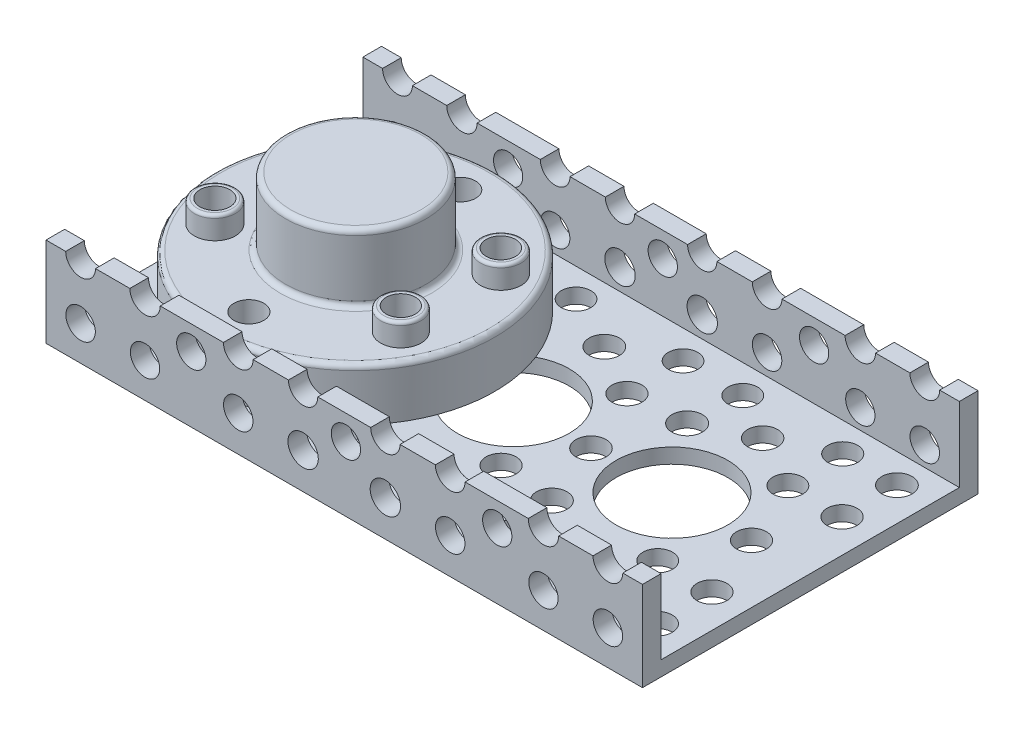
SolidWorks part; units mm, degrees
ref_plane "Front Plane" through (0, 0, 0) normal (0, 0, 1) x (1, 0, 0)
ref_plane "Top Plane" through (0, 0, 0) normal (0, 1, 0) x (1, 0, 0)
ref_plane "Right Plane" through (0, 0, 0) normal (1, 0, 0) x (0, 0, -1)
sketch "Sketch1" plane through (0, 0, 0) normal (0, 1, 0) x (1, 0, 0)
  line L1 (-56.0638, 18.2447) -> (23.9362, 18.2447)
  line L2 (-56.0638, 18.2447) -> (-56.0638, -26.7553)
  line L3 (-56.0638, -26.7553) -> (23.9362, -26.7553)
  line L4 (23.9362, 18.2447) -> (23.9362, -26.7553)
  dimension "D1" = 80
  dimension "D2" = 45
extrude "Boss-Extrude1" add sketch "Sketch1" along normal blind 2
sketch "Sketch2" plane through (0, 2, 0) normal (0, 1, 0) x (1, 0, 0)
  line L0 (-56.0638, 18.2447) -> (-56.0638, -26.7553) construction
  line L1 (-56.0638, -24.2553) -> (23.9362, -24.2553)
  line L2 (-56.0638, -24.2553) -> (-56.0638, -26.7553)
  line L3 (-56.0638, -26.7553) -> (23.9362, -26.7553)
  line L4 (23.9362, -24.2553) -> (23.9362, -26.7553)
  line L5 (-56.0638, -4.2553) -> (26.7837, -4.2553)
  line L6 (-56.0638, 18.2447) -> (23.9362, 18.2447)
  line L7 (23.9362, 15.7447) -> (23.9362, 18.2447)
  line L8 (-56.0638, 15.7447) -> (23.9362, 15.7447)
  line L9 (-56.0638, 15.7447) -> (-56.0638, 18.2447)
  line M6 (-56.0638, 18.2447) -> (-56.0638, -26.7553)
  line M7 (-56.0638, -26.7553) -> (23.9362, -26.7553)
  line M8 (23.9362, -26.7553) -> (23.9362, 18.2447)
  line M9 (23.9362, 18.2447) -> (-56.0638, 18.2447)
  dimension "D1" = 2.5
extrude "Boss-Extrude2" add sketch "Sketch2" along normal blind 10 contours L8 M6 M8 M9 | L1 M6 M7 M8
sketch "Sketch3" plane through (0, 2, 0) normal (0, 1, 0) x (1, 0, 0)
  line L0 (-56.0638, -4.2553) -> (26.7837, -4.2553) construction
  line L1 (-16.0638, 15.7447) -> (-16.0638, -15.7208)
  line L2 (-56.0638, 15.7447) -> (23.9362, 15.7447) construction
  circle A0 centre (-37.1174, -4.2553) radius 7.5
  circle A1 centre (-16.0191, -4.1212) radius 7.5
  circle A2 centre (5.258, -4.1212) radius 7.5
extrude "Cut-Extrude1" cut sketch "Sketch3" against normal blind 4 contours A0 | L1 A1 | L1 A1 | A2
sketch "Sketch4" plane through (0, 2, 0) normal (0, 1, 0) x (1, 0, 0)
  circle A0 centre (-48.1015, -4.382) radius 2
  circle A1 centre (-26.5885, -4.3897) radius 1.9841
  circle A2 centre (-5.3351, -4.3897) radius 2.0194
  circle A3 centre (16.1333, -4.3274) radius 2.0071
extrude "Cut-Extrude2" cut sketch "Sketch4" against normal blind 4 contours A0 | A1 | A2 | A3
sketch "Sketch5" plane through (0, 2, 0) normal (0, 1, 0) x (1, 0, 0)
  line L0 (-16.0638, 15.7447) -> (-16.0638, -15.8512)
  line L1 (-56.0638, 15.7447) -> (23.9362, 15.7447) construction
  line L2 (-56.0638, 15.7447) -> (23.9362, 15.7447)
  line L3 (23.9362, -4.2553) -> (1.0243, -4.2553)
  line L4 (-56.0638, -4.2553) -> (26.7837, -4.2553) construction
  circle A0 centre (12.2086, 4.4705) radius 1.9878
  circle A1 centre (19.4763, 4.4705) radius 2.0098
  circle A2 centre (12.2086, 11.8307) radius 1.9991
  circle A3 centre (19.4763, 11.8307) radius 2.0289
  circle A4 centre (-51.604, 4.4705) radius 2.0098
  circle A5 centre (-44.3363, 4.4705) radius 1.9878
  circle A6 centre (-51.604, 11.8307) radius 2.0289
  circle A7 centre (-44.3363, 11.8307) radius 1.9991
  circle A8 centre (-44.3363, -12.9811) radius 1.9878
  circle A9 centre (-51.604, -12.9811) radius 2.0098
  circle A10 centre (-51.604, -20.3414) radius 2.0289
  circle A11 centre (-44.3363, -20.3414) radius 1.9991
  circle A12 centre (12.2086, -12.9811) radius 1.9878
  circle A13 centre (19.4763, -12.9811) radius 2.0098
  circle A14 centre (19.4763, -20.3414) radius 2.0289
  circle A15 centre (12.2086, -20.3414) radius 1.9991
  point P15 (-16.0638, 15.7447)
extrude "Cut-Extrude3" cut sketch "Sketch5" against normal blind 4 contours A6 | A7 | A4 | A5 | A2 | A3 | A0 | A1 | A12 | A13 | A15 | A14 | A9 | A8 | A10 | A11
sketch "Sketch6" plane through (0, 2, 0) normal (0, 1, 0) x (1, 0, 0)
  line L0 (-16.4801, 15.7447) -> (-16.4801, -2.6196)
  line L1 (-56.0638, 15.7447) -> (23.9362, 15.7447) construction
  line L2 (26.7837, -4.2553) -> (5.258, -4.1212)
  circle A0 centre (-9.2605, 4.3606) radius 2.006
  circle A1 centre (-1.7742, 4.9442) radius 2.0446
  circle A2 centre (-9.3039, 11.9267) radius 1.9815
  circle A3 centre (-1.2727, 11.9049) radius 1.9859
  circle A4 centre (-23.6997, 4.3606) radius 2.006
  circle A5 centre (-31.186, 4.9442) radius 2.0446
  circle A6 centre (-31.6875, 11.9049) radius 1.9859
  circle A7 centre (-23.6563, 11.9267) radius 1.9815
  circle A8 centre (-23.8539, -19.8076) radius 1.9815
  circle A9 centre (-31.8843, -19.6858) radius 1.9859
  circle A10 centre (-31.2961, -12.7319) radius 2.0446
  circle A11 centre (-23.8031, -12.2416) radius 2.006
  circle A12 centre (-9.365, -12.4215) radius 2.006
  circle A13 centre (-1.8866, -13.0983) radius 2.0446
  circle A14 centre (-1.4718, -20.0648) radius 1.9859
  circle A15 centre (-9.5027, -19.9864) radius 1.9815
extrude "Cut-Extrude4" cut sketch "Sketch6" against normal blind 4 contours A6 | A7 | A5 | A4 | A2 | A3 | A1 | A0 | A12 | A13 | A15 | A14 | A8 | A11 | A10 | A9
sketch "Sketch7" plane through (0, 2, 0) normal (0, 1, 0) x (1, 0, 0)
  circle A0 centre (-37.9402, 8.2887) radius 2.0167
  circle A1 centre (-16.2275, 8.2887) radius 2.0324
  circle A2 centre (5.0095, 8.2887) radius 2.0143
  circle A3 centre (5.0095, -16.4817) radius 1.9538
  circle A4 centre (-16.2275, -16.4817) radius 2.0446
  circle A5 centre (-37.9402, -16.4817) radius 2.0378
extrude "Cut-Extrude5" cut sketch "Sketch7" against normal blind 4
sketch "Sketch8" plane through (0, 0, 26.7553) normal (0, 0, 1) x (1, 0, 0)
  line L0 (-16.0638, 12) -> (-16.0638, -5.9199)
  line L1 (-56.0638, 12) -> (23.9362, 12) construction
  circle A0 centre (-51.4232, 4.6434) radius 1.9775
  circle A1 centre (-42.781, 4.6653) radius 1.9664
  circle A2 centre (-30.2785, 4.7971) radius 1.9737
  circle A3 centre (-21.5788, 4.8411) radius 2.0361
  circle A4 centre (-36.5835, 8.7883) radius 1.962
  circle A5 centre (-51.4232, 12) radius 1.9998
  circle A6 centre (-42.781, 12) radius 2.0394
  circle A7 centre (-30.2785, 12) radius 1.9925
  circle A8 centre (-21.5788, 12) radius 1.9667
  circle A9 centre (19.2956, 4.6434) radius 1.9775
  circle A10 centre (10.6533, 4.6653) radius 1.9664
  circle A11 centre (-1.8492, 4.7971) radius 1.9737
  circle A12 centre (-10.5489, 4.8411) radius 2.0361
  circle A13 centre (-10.5489, 12) radius 1.9667
  circle A14 centre (4.4558, 8.7883) radius 1.962
  circle A15 centre (-1.8492, 12) radius 1.9925
  circle A16 centre (10.6533, 12) radius 2.0394
  circle A17 centre (19.2956, 12) radius 1.9998
  line M3 (23.9362, 12) -> (-56.0638, 12)
extrude "Cut-Extrude6" cut sketch "Sketch8" against normal blind 47 contours A5 M3 | A5 M3 | A6 M3 | A6 M3 | A7 M3 | A7 M3 | A8 M3 | A8 M3 | A13 M3 | A13 M3 | A15 M3 | A15 M3 | A14 | A16 M3 | A16 M3 | A17 M3 | A17 M3 | A9 | A10 | A11 | A12 | A2 | A3 | A4 | A1 | A0
sketch "Sketch9" plane through (0, 0, 26.7553) normal (0, 0, 1) x (1, 0, 0)
  circle A0 centre (-15.8423, 8.7037) radius 1.9641
extrude "Cut-Extrude7" cut sketch "Sketch9" against normal blind 47 contours A0
sketch "Sketch10" plane through (0, 2, 0) normal (0, 1, 0) x (1, 0, 0)
  circle A0 centre (-37.1174, -4.2553) radius 18.7462
extrude "Boss-Extrude3" add sketch "Sketch10" along normal blind 7
sketch "Sketch11" plane through (0, 9, 0) normal (0, 1, 0) x (1, 0, 0)
  circle A0 centre (-37.1621, -4.0989) radius 9.4368
extrude "Boss-Extrude4" add sketch "Sketch11" along normal blind 9 contours A0
fillet "Fillet1" radius 0.7 3 edges at (-37.1621, 9, 13.5356) (-37.1621, 18, 13.5356) (-37.1174, 9, 23.0015)
sketch "Sketch12" plane through (0, 9, 0) normal (0, 1, 0) x (1, 0, 0)
  circle A0 centre (-37.1174, 9.8922) radius 2.0214
  circle A1 centre (-37.1174, -18.4922) radius 2.0015
extrude "Cut-Extrude8" cut sketch "Sketch12" against normal blind 5
sketch "Sketch13" plane through (0, 9, 0) normal (0, 1, 0) x (1, 0, 0)
  circle A0 centre (-49.5886, 2.8296) radius 2.009
  circle A1 centre (-49.5886, -10.5803) radius 2.0035
  circle A2 centre (-24.6462, -10.5803) radius 1.9607
  circle A3 centre (-24.6462, 2.8296) radius 1.9759
  circle A4 centre (-24.6462, 2.8296) radius 2.7259
  circle A5 centre (-49.5886, 2.8296) radius 2.759
  circle A6 centre (-49.5886, -10.5803) radius 2.7535
  circle A7 centre (-24.6462, -10.5803) radius 2.7107
  dimension "D1" = 0.75
extrude "Boss-Extrude5" add sketch "Sketch13" along normal blind 3
fillet "Fillet2" radius 0.4 4 edges at (-49.5886, 12, -0.0706) (-49.5886, 12, 13.3339) (-24.6462, 12, -0.1037) (-24.6462, 12, 13.291)
